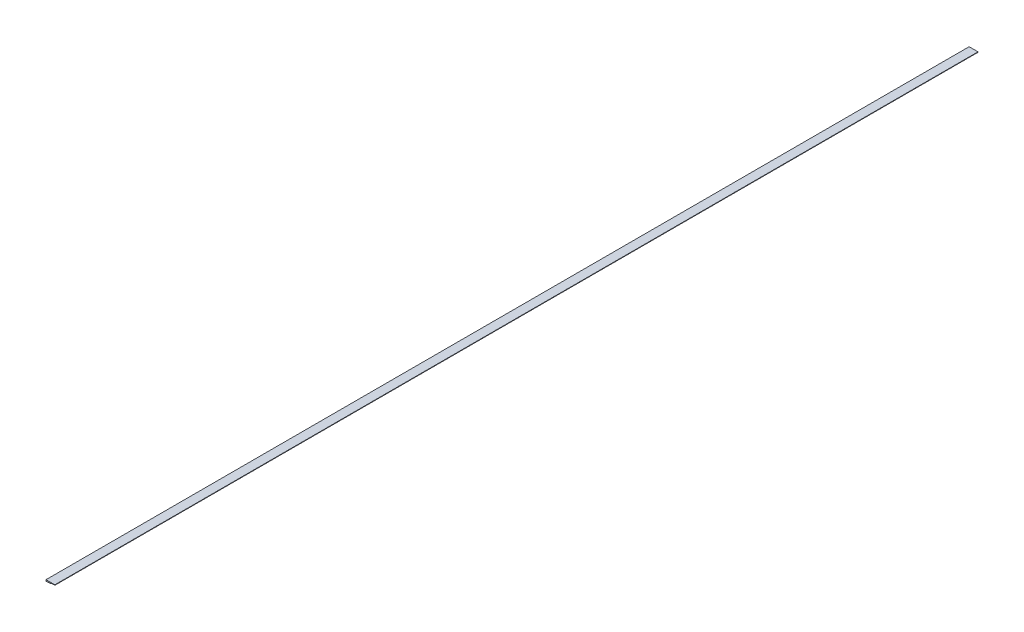
SolidWorks part; units mm, degrees
material "ASTM A500 Grade B Steel"
ref_plane "Front Plane" through (0, 0, 0) normal (0, 0, 1) x (1, 0, 0)
ref_plane "Top Plane" through (0, 0, 0) normal (0, 1, 0) x (1, 0, 0)
ref_plane "Right Plane" through (0, 0, 0) normal (1, 0, 0) x (0, 0, -1)
sketch "Sketch2" plane through (0, 0, 0) normal (0, 0, 1) x (1, 0, 0)
  line L0 (-7.6194, 25.4) -> (-32.6194, 23.2128)
  line L1 (-2103.2445, -157.9434) -> (-7.6194, 25.4) construction
  line L2 (-7.6194, 25.4) -> (-4.4444, 25.4)
  line L3 (-4.4444, 25.4) -> (-4.4444, 28.575)
  line L4 (-4.4444, 28.575) -> (17.3806, 28.575)
  line L5 (-4.4444, 28.575) -> (112.1612, 28.575) construction
  line L6 (17.3806, 28.575) -> (17.3806, 31.0863)
  line L7 (17.3806, 31.0863) -> (-32.6194, 31.0863)
  line L8 (-32.6194, 31.0863) -> (-32.6194, 23.2128)
  point P16 (-7.0204, 24.7523)
  dimension "D1" = 25
  dimension "D2" = 25
extrude "Boss-Extrude1" add sketch "Sketch2" against normal up to surface (5214.4 mm away)
